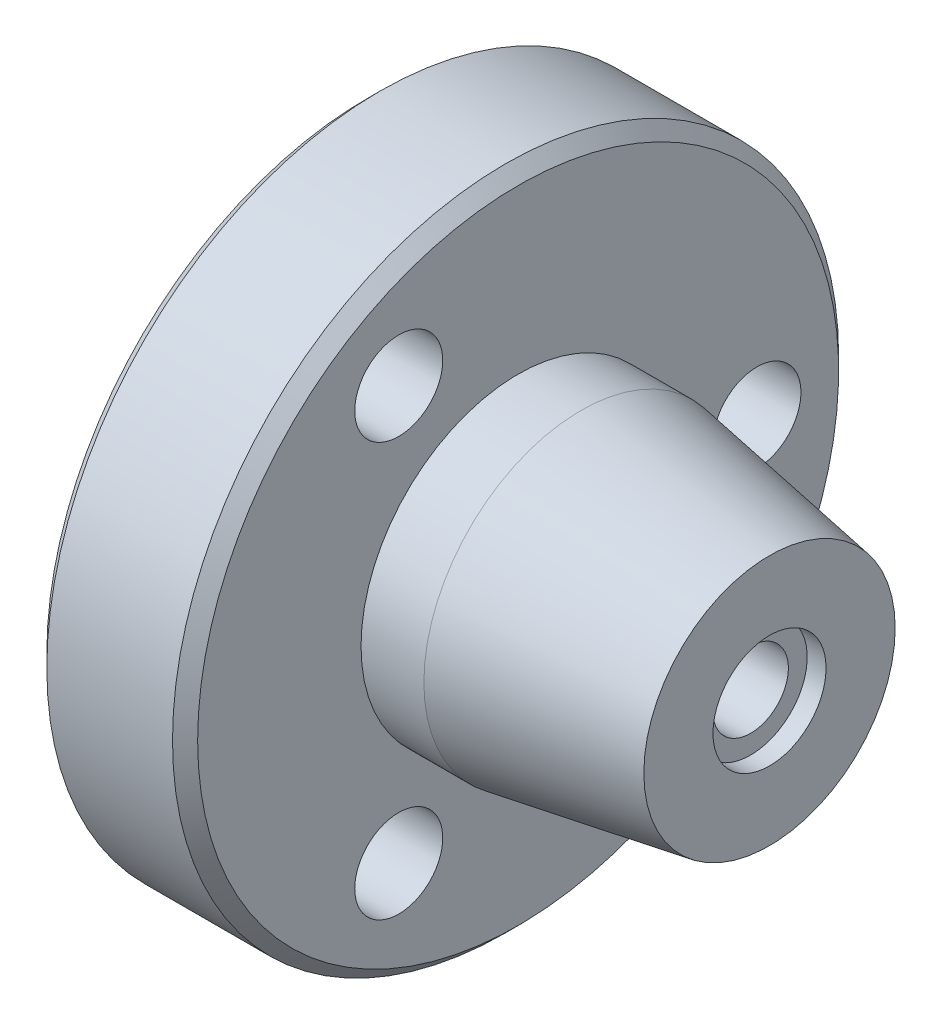
SolidWorks part; units mm, degrees
ref_plane "前视基准面" through (0, 0, 0) normal (0, 0, 1) x (1, 0, 0)
ref_plane "上视基准面" through (0, 0, 0) normal (0, 1, 0) x (1, 0, 0)
ref_plane "右视基准面" through (0, 0, 0) normal (1, 0, 0) x (0, 0, -1)
sketch "草图1" plane through (0, 0, 0) normal (0, 0, 1) x (1, 0, 0)
  line L0 (0, 11.5) -> (1, 12.5)
  line L1 (1, 12.5) -> (8, 12.5)
  line L2 (8, 12.5) -> (8, 25.5)
  line L3 (8, 25.5) -> (9, 26.5)
  line L4 (9, 26.5) -> (19, 26.5)
  line L5 (19, 26.5) -> (20, 25.5)
  line L6 (20, 25.5) -> (20, 12.5)
  line L7 (20, 12.5) -> (25, 12.5)
  line L8 (25, 12.5) -> (40, 10)
  line L9 (40, 10) -> (40, 4.5)
  line L10 (40, 4.5) -> (38.5, 4.5)
  line L11 (38.5, 4.5) -> (38.5, 3)
  line L12 (38.5, 3) -> (1.5, 3)
  line L13 (1.5, 3) -> (1.5, 4.5)
  line L14 (1.5, 4.5) -> (0, 4.5)
  line L15 (0, 4.5) -> (0, 11.5)
  line L16 (0, 0) -> (40, 0) construction
revolve "旋转1" add sketch "草图1" angle 360 about L16
sketch "草图2" plane through (0, 0, 0) normal (1, 0, 0) x (0, 0, -1)
  circle A0 centre (19, 0) radius 3.5
  circle A1 centre (-9.5, 16.4545) radius 3.5
  circle A2 centre (-9.5, -16.4545) radius 3.5
extrude "切除-拉伸1" cut sketch "草图2" along normal through all
